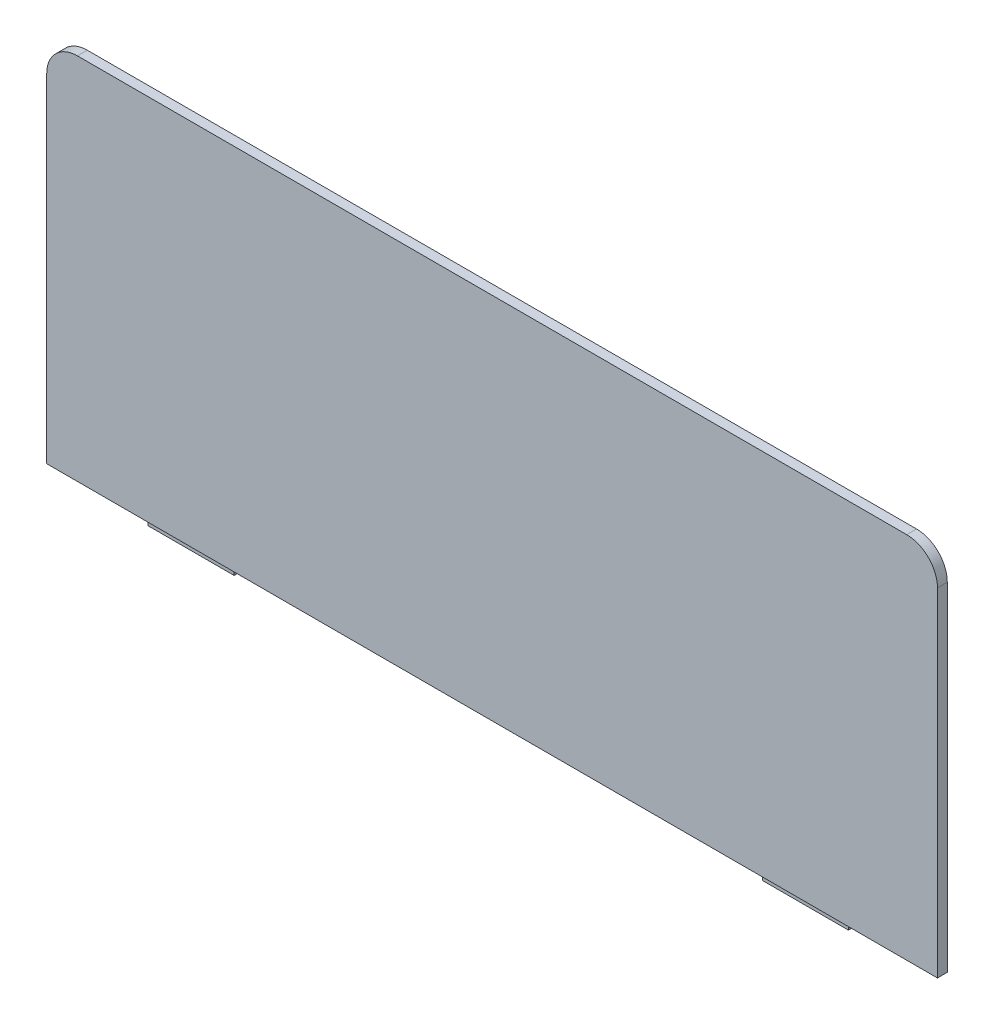
SolidWorks part; units mm, degrees
other "标注1"
sketch "草图5" plane through (-166.2025, 72.3769, -6.5) normal (-0.4469, 0.8726, -0.1973) x (0.0508, 0.2449, 0.9682)
ref_plane "前视基准面" through (0, 0, 0) normal (0, 0, 1) x (1, 0, 0)
ref_plane "上视基准面" through (0, 0, 0) normal (0, 1, 0) x (1, 0, 0)
ref_plane "右视基准面" through (0, 0, 0) normal (1, 0, 0) x (0, 0, -1)
sketch "草图1" plane through (0, 0, 0) normal (0, 0, 1) x (1, 0, 0)
  line L0 (-107.2025, -47.6231) -> (64.7975, -47.6231)
  line L1 (-156.2025, 72.3769) -> (113.7975, 72.3769)
  line L2 (-166.2025, 62.3769) -> (-166.2025, -47.6231)
  line L3 (-166.2025, -47.6231) -> (-135.2025, -47.6231)
  line L4 (123.7975, 62.3769) -> (123.7975, -47.6231)
  line L6 (-135.2025, -47.6231) -> (-135.2025, -50.6231)
  line L7 (-135.2025, -50.6231) -> (-107.2025, -50.6231)
  line L8 (-107.2025, -47.6231) -> (-107.2025, -50.6231)
  line L10 (92.7975, -47.6231) -> (92.7975, -50.6231)
  line L11 (92.7975, -50.6231) -> (64.7975, -50.6231)
  line L12 (64.7975, -47.6231) -> (64.7975, -50.6231)
  line L13 (92.7975, -47.6231) -> (123.7975, -47.6231)
  arc A0 (113.7975, 72.3769) -> (123.7975, 62.3769) centre (113.7975, 62.3769) cw
  arc A1 (-156.2025, 72.3769) -> (-166.2025, 62.3769) centre (-156.2025, 62.3769) ccw
  point P6 (123.7975, 72.3769)
  dimension "D3" = 10
  dimension "D1" = 120
  dimension "D2" = 290
  dimension "D4" = 31
  dimension "D5" = 28
  dimension "D6" = 3
  dimension "D7" = 31
  dimension "D8" = 28
  dimension "D9" = 3
extrude "凸台-拉伸1" add sketch "草图1" along normal blind 3.2
sketch "草图2" plane through (0, 0, 3.2) normal (0, 0, 1) x (1, 0, 0)
  line L0 (92.7975, -50.6231) -> (92.7975, -47.6231) construction
  line L1 (-135.2025, -50.6231) -> (-107.2025, -50.6231)
  line L2 (-135.2025, -50.6231) -> (-135.2025, -47.6231)
  line L3 (-135.2025, -47.6231) -> (-107.2025, -47.6231)
  line L4 (-107.2025, -50.6231) -> (-107.2025, -47.6231)
  line L5 (64.7975, -50.6231) -> (92.7975, -50.6231)
  line L6 (64.7975, -50.6231) -> (64.7975, -47.6231)
  line L7 (64.7975, -47.6231) -> (92.7975, -47.6231)
  line L8 (92.7975, -50.6231) -> (92.7975, -47.6231)
extrude "切除-拉伸1" cut sketch "草图2" against normal blind 2
sketch "草图3" plane through (0, 0, 0) normal (0, 0, 1) x (1, 0, 0)
  line L0 (113.7975, 72.3769) -> (-156.2025, 72.3769) construction
  line L1 (-132.4025, 19.3769) -> (-127.4025, 19.3769)
  line L2 (-132.4025, 19.3769) -> (-132.4025, 7.3769)
  line L3 (-132.4025, 7.3769) -> (-127.4025, 7.3769)
  line L4 (-127.4025, 19.3769) -> (-127.4025, 7.3769)
  line L5 (89.9975, 19.3769) -> (84.9975, 19.3769)
  line L6 (89.9975, 19.3769) -> (89.9975, 7.3769)
  line L7 (89.9975, 7.3769) -> (84.9975, 7.3769)
  line L8 (84.9975, 19.3769) -> (84.9975, 7.3769)
  line L9 (-166.2025, 62.3769) -> (-166.2025, -47.6231) construction
  line L10 (123.7975, -47.6231) -> (123.7975, 62.3769) construction
  dimension "D1" = 53
  dimension "D2" = 12
  dimension "D3" = 5
  dimension "D4" = 33.8
  dimension "D5" = 33.8
extrude "凸台-拉伸2" add sketch "草图3" against normal blind 7
sketch "草图4" plane through (65.4206, 19.3769, 0) normal (0, -1, 0) x (0, 0, -1)
  line L0 (7, 19.5769) -> (0, 19.5769) construction
  line L2 (0, -192.8231) -> (0, -197.8231) construction
  line L3 (7, -197.8231) -> (0, -197.8231) construction
  circle A1 centre (4.5, -195.3231) radius 1
  circle A2 centre (4.5, 22.0769) radius 1
  point P8 (0, 0)
  point P9 (0, 0)
  dimension "D1" = 2
  dimension "D2" = 4.5
  dimension "D3" = 2.5
  dimension "D4" = 2.5
extrude "切除-拉伸2" cut sketch "草图4" along normal through all
